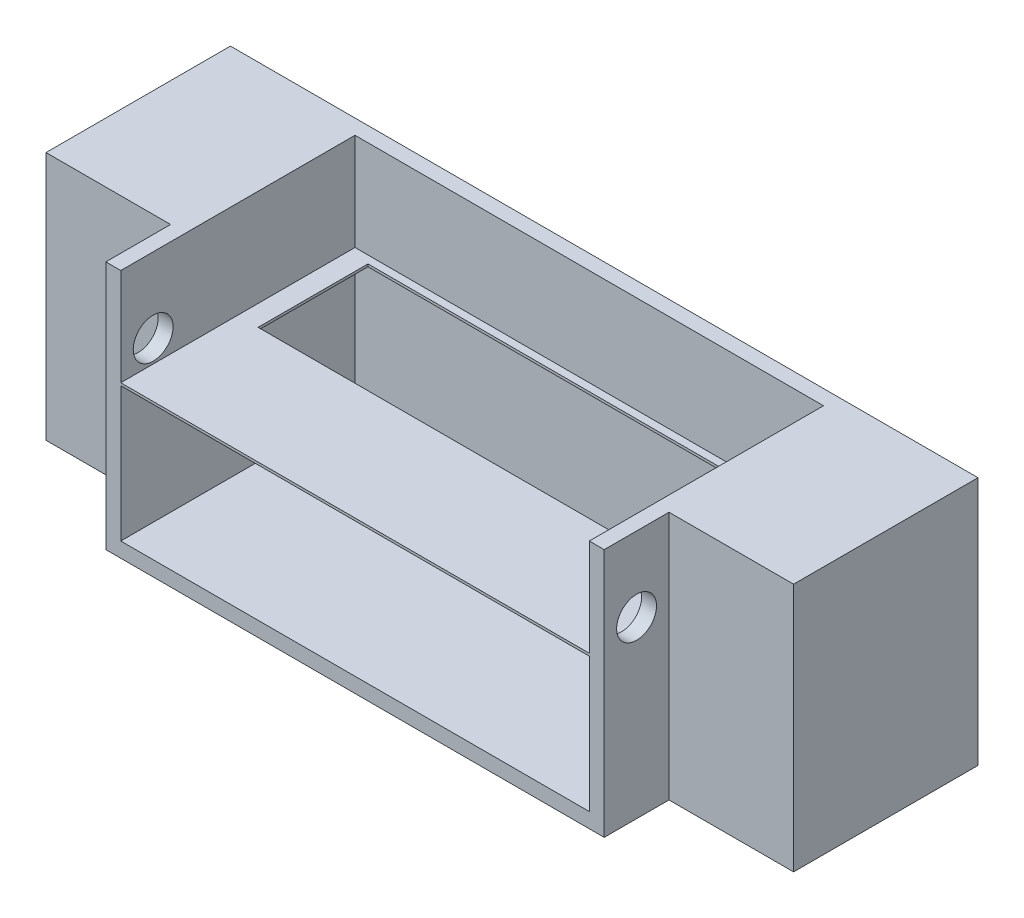
SolidWorks part; units mm, degrees
ref_plane "Front Plane" through (0, 0, 0) normal (0, 0, 1) x (1, 0, 0)
ref_plane "Top Plane" through (0, 0, 0) normal (0, 1, 0) x (1, 0, 0)
ref_plane "Right Plane" through (0, 0, 0) normal (1, 0, 0) x (0, 0, -1)
sketch "Sketch1" plane through (0, 0, 0) normal (0, 0, 1) x (1, 0, 0)
  line L1 (50, -20) -> (-50, -20)
  line L2 (50, -20) -> (50, 20)
  line L3 (50, 20) -> (-50, 20)
  line L4 (-50, -20) -> (-50, 20)
  line L5 (50, -20) -> (-50, 20) construction
  line L6 (50, 20) -> (-50, -20) construction
  point P0 (0, 0)
  dimension "D1" = 100
  dimension "D2" = 40
extrude "Boss-Extrude1" add sketch "Sketch1" against normal blind 50
sketch "Sketch2" plane through (0, 20, 0) normal (0, 1, 0) x (1, 0, 0)
  line L0 (50, 50) -> (-50, 50) construction
  line L1 (47, 0) -> (-47, 0)
  line L2 (47, 0) -> (47, 47)
  line L3 (47, 47) -> (-47, 47)
  line L4 (-47, 0) -> (-47, 47)
  line L5 (47, 0) -> (-47, 47) construction
  line L6 (47, 47) -> (-47, 0) construction
  line L8 (50, 50) -> (50, 0) construction
  line L9 (-50, 50) -> (-50, 0) construction
  line L10 (50, 0) -> (-50, 0) construction
  point P0 (0, 23.5)
  point P7 (0, 0)
  point P9 (50, 41.8881)
  dimension "D1" = 3
  dimension "D2" = 3
  dimension "D3" = 3
  dimension "D4" = 0
extrude "Cut-Extrude1" cut sketch "Sketch2" against normal blind 37
sketch "Sketch3" plane through (50, 0, 0) normal (1, 0, 0) x (0, 0, -1)
  line L0 (50, -20) -> (50, 20) construction
  line L1 (50, -20) -> (13, -20)
  line L2 (50, -20) -> (50, 20)
  line L3 (50, 20) -> (13, 20)
  line L4 (13, -20) -> (13, 20)
  line L5 (50, -20) -> (13, 20) construction
  line L6 (50, 20) -> (13, -20) construction
  point P0 (31.5, 0)
  dimension "D1" = 0
  dimension "D2" = 0
  dimension "D3" = 0
  dimension "D4" = 37
extrude "Boss-Extrude2" add sketch "Sketch3" along normal blind 25
ref_plane "Plane1" through (0, 0, 0) normal (-1, 0, 0) x (0, 0, 1)
mirror "Mirror2" about plane through (0, 0, 0) normal (-1, 0, 0) of "Boss-Extrude2"
sketch "Sketch4" plane through (-50, 0, 0) normal (-1, 0, 0) x (0, 0, 1)
  line L0 (-13, 20) -> (0, 20) construction
  line L1 (0, 20) -> (0, -20) construction
  circle A0 centre (-6.5, 15) radius 4
  dimension "D1" = 5
  dimension "D2" = 6.5
extrude "Cut-Extrude2" cut sketch "Sketch4" against normal through all
ref_point "Point1"
sketch "Sketch6" plane through (0, 20, 0) normal (0, 1, 0) x (1, 0, 0)
  line L12 (-47, 0) -> (-47, 47)
  line L13 (-47, 47) -> (47, 47)
  line L14 (47, 47) -> (47, 0)
  line L15 (47, 0) -> (50, 0)
  line L16 (50, 0) -> (50, 13)
  line L17 (50, 13) -> (75, 13)
  line L18 (75, 13) -> (75, 50)
  line L19 (75, 50) -> (-75, 50)
  line L20 (-75, 50) -> (-75, 13)
  line L21 (-75, 13) -> (-50, 13)
  line L22 (-50, 13) -> (-50, 0)
  line L23 (-50, 0) -> (-47, 0)
  line L24 (-47, 0) -> (-47, 47)
  line L25 (-47, 47) -> (47, 47)
  line L26 (47, 47) -> (47, 0)
  line L27 (47, 0) -> (50, 0)
  line L28 (50, 0) -> (50, 13)
  line L29 (50, 13) -> (75, 13)
  line L30 (75, 13) -> (75, 50)
  line L31 (75, 50) -> (-75, 50)
  line L32 (-75, 50) -> (-75, 13)
  line L33 (-75, 13) -> (-50, 13)
  line L34 (-50, 13) -> (-50, 0)
  line L35 (-50, 0) -> (-47, 0)
  dimension "D1" = 0
extrude "Boss-Extrude3" add sketch "Sketch6" along normal blind 10
sketch "Sketch7" plane through (0, 0, 0) normal (0, 0, 1) x (1, 0, 0)
  line L0 (75, -20) -> (50, -20) construction
  line L1 (47, 10) -> (-47, 10)
  line L2 (47, 10) -> (47, 10.5)
  line L3 (47, 10.5) -> (-47, 10.5)
  line L4 (-47, 10) -> (-47, 10.5)
  line L5 (47, 10) -> (-47, 10.5) construction
  line L6 (47, 10.5) -> (-47, 10) construction
  line L7 (-50, -20) -> (50, -20) construction
  point P0 (0, 10.25)
  dimension "D1" = 30
  dimension "D2" = 30.5
  dimension "D3" = 0
  dimension "D4" = 0
extrude "Boss-Extrude4" add sketch "Sketch7" against normal up to next
sketch "Sketch8" plane through (0, 10.5, 0) normal (0, 1, 0) x (1, 0, 0)
  line L0 (0, 14.85) -> (0, -14.85) construction
  line L1 (42.8499, 23.4114) -> (-42.8499, 23.4114)
  line L2 (42.8499, 23.4114) -> (42.8499, 45.4518)
  line L3 (42.8499, 45.4518) -> (-42.8499, 45.4518)
  line L4 (-42.8499, 23.4114) -> (-42.8499, 45.4518)
  line L5 (42.8499, 23.4114) -> (-42.8499, 45.4518) construction
  line L6 (42.8499, 45.4518) -> (-42.8499, 23.4114) construction
  point P0 (0, 34.4316)
  point P7 (42.8499, 23.4114)
extrude "Cut-Extrude3" cut sketch "Sketch8" against normal up to next
